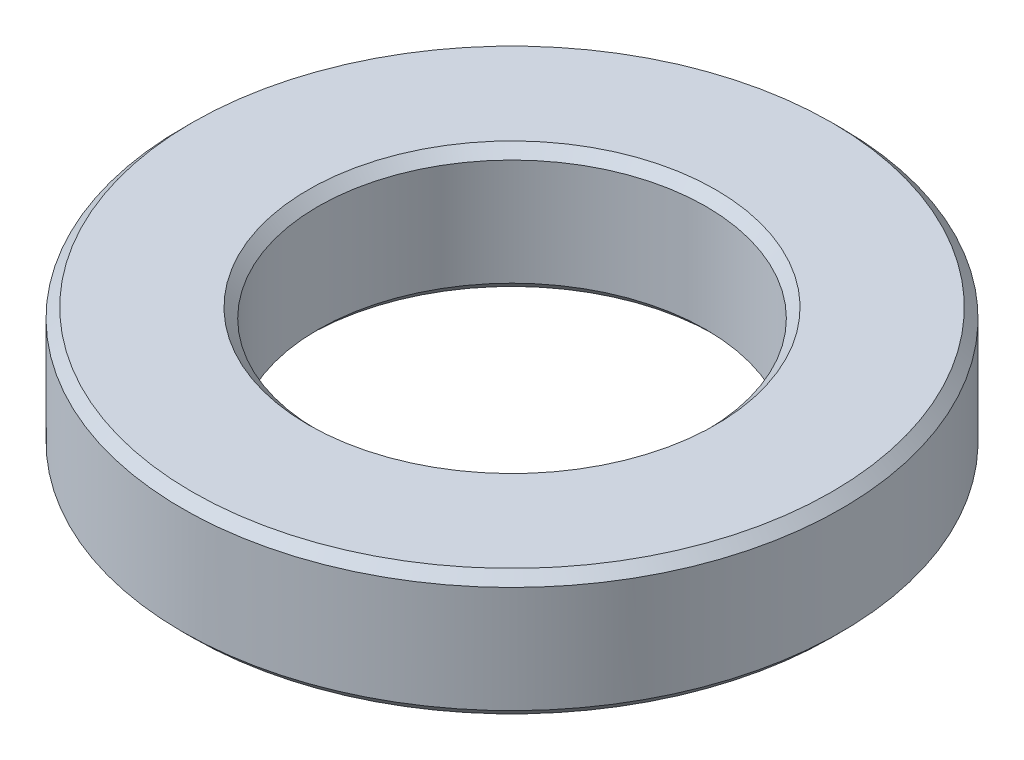
SolidWorks part; units mm, degrees
ref_plane "前视基准面" through (0, 0, 0) normal (0, 0, 1) x (1, 0, 0)
ref_plane "上视基准面" through (0, 0, 0) normal (0, 1, 0) x (1, 0, 0)
ref_plane "右视基准面" through (0, 0, 0) normal (1, 0, 0) x (0, 0, -1)
other "Configuration Table"
sketch "草图1" plane through (0, 0, 0) normal (0, 1, 0) x (1, 0, 0)
  circle A0 centre (0, 0) radius 33.99
  circle A1 centre (0, 0) radius 20.01
  dimension "D1" = 40.02
  dimension "D2" = 67.98
extrude "凸台-拉伸1" add sketch "草图1" along normal blind 13
chamfer "倒角1" distance 1 angle 45 4 edges at (0, 0, 33.99) (0, 13, 33.99) (0, 0, 20.01) (0, 13, 20.01)
